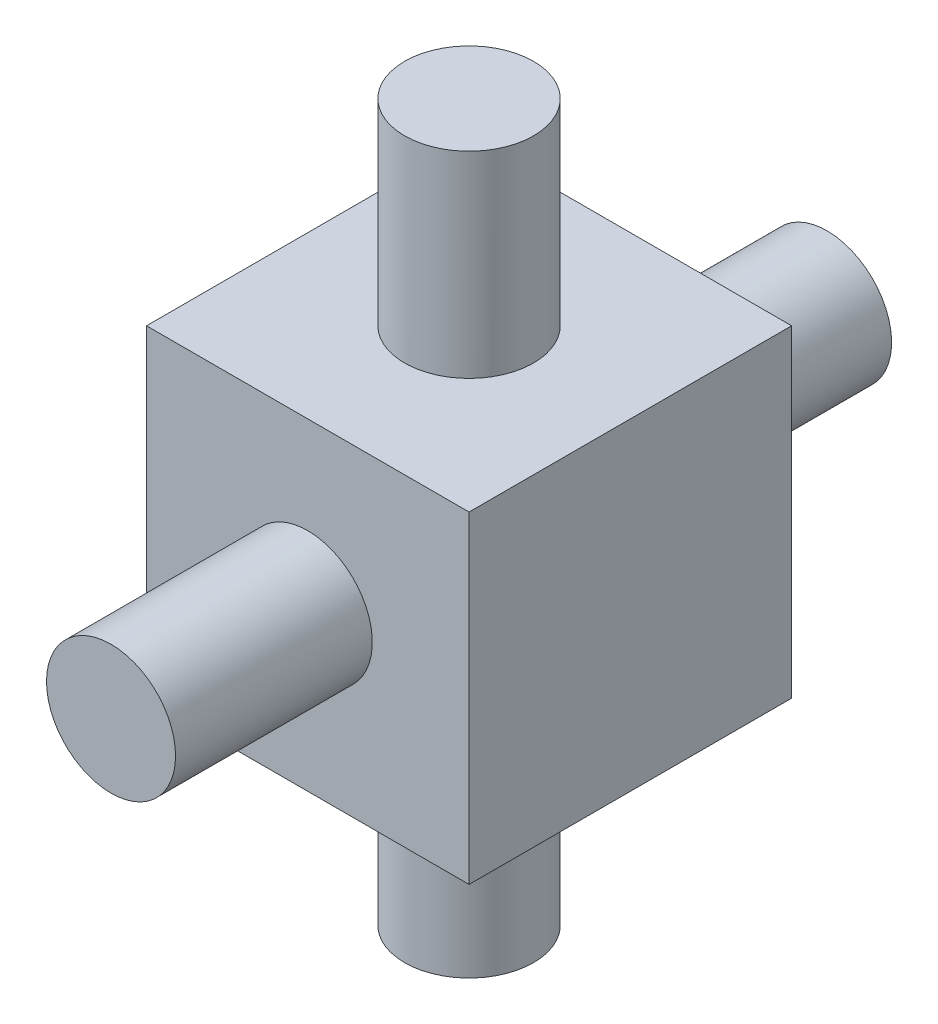
SolidWorks part; units mm, degrees
material "Bronze commercial, UNS C22000 (90-10 Bronze)"
ref_plane "Plan de face" through (0, 0, 0) normal (0, 0, 1) x (1, 0, 0)
ref_plane "Plan de dessus" through (0, 0, 0) normal (0, 1, 0) x (1, 0, 0)
ref_plane "Plan de droite" through (0, 0, 0) normal (1, 0, 0) x (0, 0, -1)
sketch "Esquisse1" plane through (0, 0, 0) normal (0, 0, 1) x (1, 0, 0)
  line L1 (0, 0) -> (5, 0)
  line L2 (0, 0) -> (0, 5)
  line L3 (0, 5) -> (5, 5)
  line L4 (5, 0) -> (5, 5)
  dimension "D1" = 5
  dimension "D2" = 5
extrude "Boss.-Extru.1" add sketch "Esquisse1" along normal blind 5
sketch "Esquisse2" plane through (0, 5, 0) normal (0, 1, 0) x (1, 0, 0)
  line L0 (5, 0) -> (0, 0) construction
  line L2 (5, -5) -> (5, 0) construction
  circle A0 centre (2.5, -2.5) radius 1
  point P6 (5, -4.391)
  dimension "D1" = 2
  dimension "D2" = 2.5
  dimension "D3" = 2.5
extrude "Boss.-Extru.2" add sketch "Esquisse2" along normal blind 3.05
sketch "Esquisse3" plane through (0, 0, 0) normal (0, -1, 0) x (1, 0, 0)
  line L0 (0, 5) -> (5, 5) construction
  line L1 (0, 5) -> (0, 0) construction
  circle A0 centre (2.5, 2.5) radius 1
  dimension "D1" = 2
  dimension "D3" = 2.5
  dimension "D2" = 2.5
extrude "Boss.-Extru.3" add sketch "Esquisse3" along normal blind 3.05
sketch "Esquisse4" plane through (0, 0, 5) normal (0, 0, 1) x (1, 0, 0)
  line L0 (5, 0) -> (5, 5) construction
  line L2 (5, 5) -> (0, 5) construction
  circle A0 centre (2.5, 2.5) radius 1
  dimension "D1" = 2
  dimension "D2" = 2.5
  dimension "D3" = 2.5
extrude "Boss.-Extru.4" add sketch "Esquisse4" along normal blind 3.05
sketch "Esquisse5" plane through (0, 0, 0) normal (0, 0, -1) x (-1, 0, 0)
  line L0 (-5, 5) -> (0, 5) construction
  line L1 (0, 5) -> (0, 0) construction
  circle A0 centre (-2.5, 2.5) radius 1
  dimension "D1" = 2.5
  dimension "D2" = 2.5
extrude "Boss.-Extru.5" add sketch "Esquisse5" along normal blind 3.05
